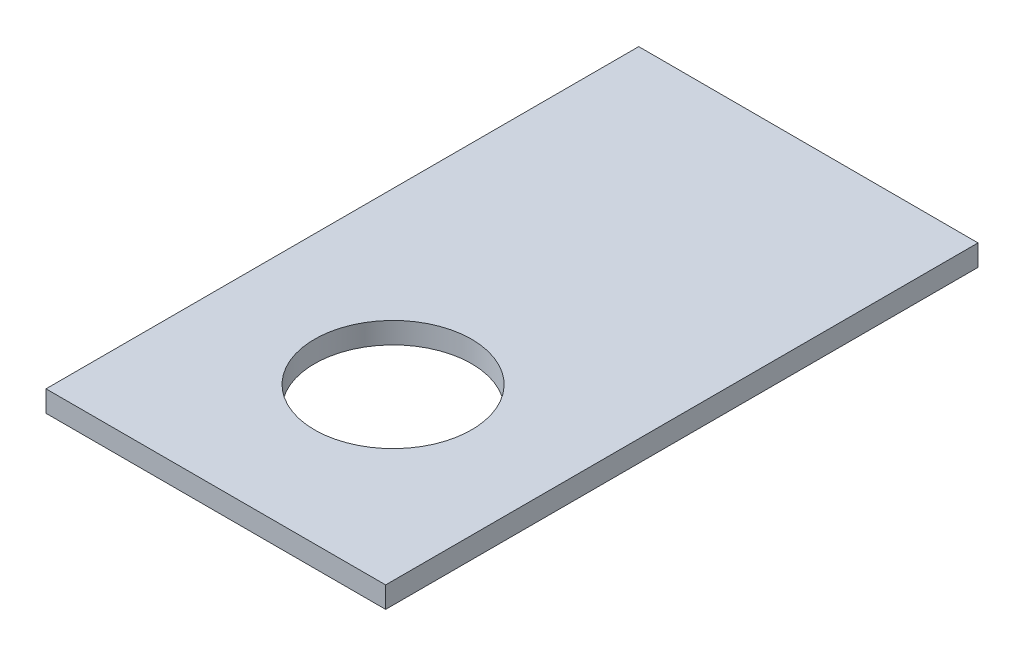
SolidWorks part; units mm, degrees
ref_plane "Front Plane" through (0, 0, 0) normal (0, 0, 1) x (1, 0, 0)
ref_plane "Top Plane" through (0, 0, 0) normal (0, 1, 0) x (1, 0, 0)
ref_plane "Right Plane" through (0, 0, 0) normal (1, 0, 0) x (0, 0, -1)
sketch "Sketch1" plane through (0, 0, 0) normal (0, 1, 0) x (1, 0, 0)
  line L0 (0, -40.3795) -> (80, -40.4673)
  line L2 (0, -40.3795) -> (0, -180)
  line L3 (0, -180) -> (80, -180)
  line L4 (80, -40.4673) -> (80, -180)
  line L5 (40, -90) -> (80, -180) construction
  line L6 (80, -180) -> (78.043, -177.852) construction
  line L7 (60, -135) -> (40, -180) construction
  line L9 (40, -90) -> (40, -174.4486) construction
  circle A0 centre (40, -131.25) radius 6
  circle A1 centre (24.5, -138.25) radius 1.525
  circle A2 centre (55.5, -138.25) radius 1.525
  circle A3 centre (32.25, -124.8266) radius 1.525
  circle A4 centre (47.75, -124.8266) radius 1.525
extrude "Boss-Extrude1" add sketch "Sketch1" along normal blind 5
sketch "Sketch2" plane through (0, 5, 0) normal (0, 1, 0) x (1, 0, 0)
  line L0 (22.3211, -134.8653) -> (40, -138.25) construction
  circle A0 centre (40, -138.25) radius 18.5
extrude "Cut-Extrude1" cut sketch "Sketch2" against normal through all both and the other way through all
